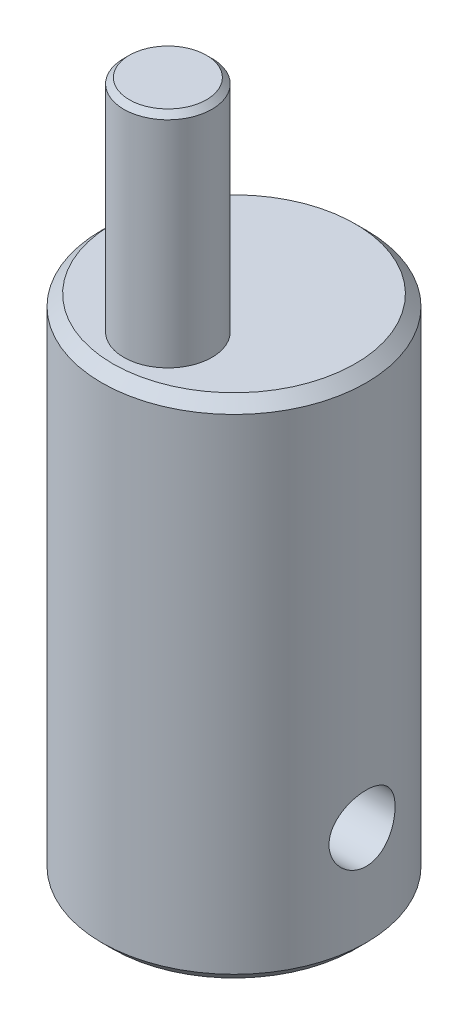
SolidWorks part; units mm, degrees
material "Gray Cast Iron"
ref_plane "Front Plane" through (0, 0, 0) normal (0, 0, 1) x (1, 0, 0)
ref_plane "Top Plane" through (0, 0, 0) normal (0, 1, 0) x (1, 0, 0)
ref_plane "Right Plane" through (0, 0, 0) normal (1, 0, 0) x (0, 0, -1)
sketch "Sketch1" plane through (0, 0, 0) normal (0, 1, 0) x (1, 0, 0)
  circle A0 centre (0, 0) radius 6
  dimension "D1" = 12
extrude "Boss-Extrude1" add sketch "Sketch1" along normal blind 23
sketch "Sketch2" plane through (0, 23, 0) normal (0, 1, 0) x (1, 0, 0)
  circle A0 centre (0, -3) radius 2
  dimension "D2" = 4
  dimension "D1" = 3
extrude "Boss-Extrude2" add sketch "Sketch2" along normal blind 10
sketch "Sketch3" plane through (0, 0, 0) normal (1, 0, 0) x (0, 0, -1)
  circle A0 centre (0, 5) radius 1.5
  dimension "D2" = 3
  dimension "D1" = 5
extrude "Cut-Extrude1" cut sketch "Sketch3" against normal through all both and the other way through all
chamfer "Chamfer1" distance 0.25 angle 45 1 edges at (0, 33, 5)
chamfer "Chamfer2" distance 0.5 angle 45 2 edges at (0, 23, 6) (0, 0, 6)
